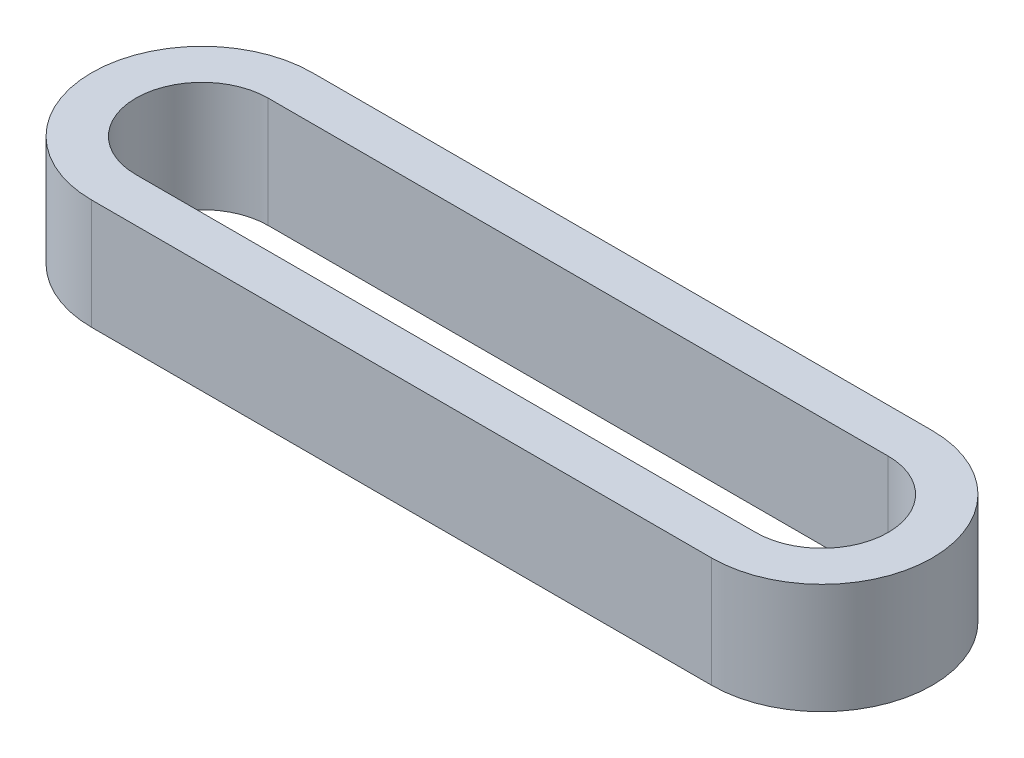
SolidWorks part; units mm, degrees
material "ABS"
ref_plane "Front" through (0, 0, 0) normal (0, 0, 1) x (1, 0, 0)
ref_plane "Top" through (0, 0, 0) normal (0, 1, 0) x (1, 0, 0)
ref_plane "Right" through (0, 0, 0) normal (1, 0, 0) x (0, 0, -1)
sketch "Sketch1" plane through (0, 0, 0) normal (0, 1, 0) x (1, 0, 0)
  line L0 (-7.025, 0) -> (7.025, 0) construction
  line L1 (-7.025, 2.5) -> (7.025, 2.5)
  line L2 (-7.025, -2.5) -> (7.025, -2.5)
  arc A0 (-7.025, 2.5) -> (-7.025, -2.5) centre (-7.025, 0) ccw
  arc A1 (7.025, -2.5) -> (7.025, 2.5) centre (7.025, 0) ccw
  point P2 (0, 0)
  dimension "D1" = 19.05
  dimension "D2" = 5
extrude "Extrude-Thin1" add sketch "Sketch1" along normal blind 2.5 thin
